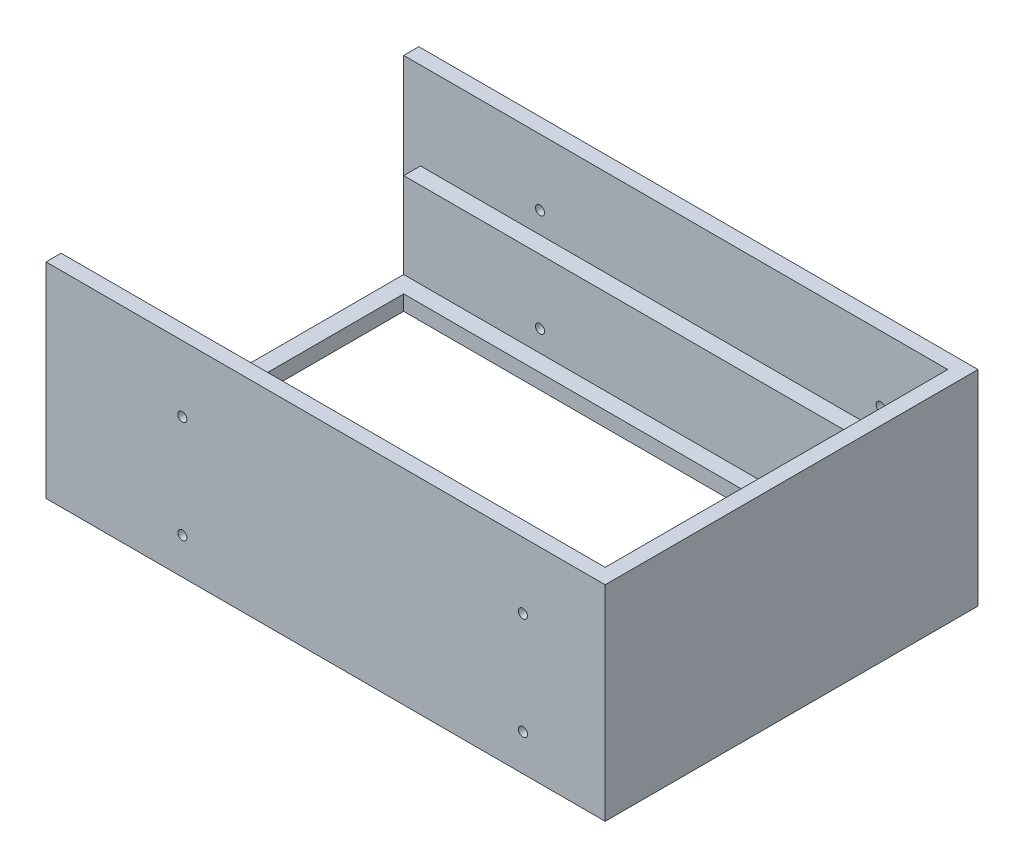
SolidWorks part; units mm, degrees
ref_plane "Front Plane" through (0, 0, 0) normal (0, 0, 1) x (1, 0, 0)
ref_plane "Top Plane" through (0, 0, 0) normal (0, 1, 0) x (1, 0, 0)
ref_plane "Right Plane" through (0, 0, 0) normal (1, 0, 0) x (0, 0, -1)
sketch "Sketch1" plane through (0, 0, 0) normal (0, 1, 0) x (1, 0, 0)
  line L1 (-83.25, 55.5) -> (83.25, 55.5)
  line L2 (-83.25, 55.5) -> (-83.25, -55.5)
  line L3 (-83.25, -55.5) -> (83.25, -55.5)
  line L4 (83.25, 55.5) -> (83.25, -55.5)
  line L5 (-83.25, 55.5) -> (83.25, -55.5) construction
  line L6 (-83.25, -55.5) -> (83.25, 55.5) construction
  point P0 (0, 0)
  dimension "D1" = 166.5
  dimension "D2" = 111
extrude "Boss-Extrude1" add sketch "Sketch1" along normal blind 30.5
shell "Shell1" thickness 4.5
sketch "Sketch2" plane through (0, 4.5, 0) normal (0, 1, 0) x (1, 0, 0)
  line L5 (78.75, 51) -> (-83.25, 51) construction
  line L6 (-78.25, 46) -> (78.75, 46)
  line L9 (-78.25, 46) -> (-78.25, -46)
  line L10 (-78.25, -46) -> (78.75, -46)
  line L11 (78.75, 46) -> (78.75, -46)
  line L12 (-83.25, -51) -> (78.75, -51) construction
  line L13 (-83.25, 51) -> (-83.25, -51) construction
  line L14 (78.75, -51) -> (78.75, 51) construction
  point P0 (0, 0)
  dimension "D1" = 5
  dimension "D2" = 5
  dimension "D3" = 5
extrude "Cut-Extrude1" cut sketch "Sketch2" against normal up to next
hole_wizard "Tap Drill for #6-32 Tap1" positions "Sketch4" profile "Sketch5" hole size "#6-32" standard "ANSI Inch"
sketch "Sketch4" plane through (0, 0, -55.5) normal (0, 0, -1) x (-1, 0, 0)
  line L0 (-78.75, 4.5) -> (83.25, 4.5) construction
  line L2 (-78.75, 30.5) -> (-78.75, 4.5) construction
  point P0 (42.66, 10.84)
  point P2 (-58.75, 10.84)
  dimension "D1" = 6.34
  dimension "D2" = 20
  dimension "D3" = 101.41
sketch "Sketch5" plane through (-42.66, 10.84, -55.5) normal (1, 0, 0) x (0, 1, 0)
  line L0 (0, 0) -> (0, 4.5)
  line L1 (0, 4.5) -> (1.3525, 4.5)
  line L2 (1.3525, 4.5) -> (1.3525, 0)
  line L5 (1.3525, 0) -> (0, 0)
  line L11 (0, -6.35) -> (0, 107.95) construction
  dimension "Thru Hole Dia." = 2.7051
  dimension "Thru Hole Depth" = 4.5
mirror "Mirror1" about plane through (0, 0, 0) normal (0, 0, 1) of "Tap Drill for #6-32 Tap1"
pattern_linear "LPattern1" count 2 spacing 30.5 along (0, 1, 0) of bodies 104
combine bodies "Combine1" operation type add bodies to combine 104 105
sketch "Sketch7" plane through (-83.25, 0, 0) normal (-1, 0, 0) x (0, 0, 1)
  line L1 (-51, 30.5) -> (51, 30.5)
  line L2 (-51, 30.5) -> (-51, 35)
  line L3 (-51, 35) -> (51, 35)
  line L4 (51, 30.5) -> (51, 35)
extrude "Cut-Extrude2" cut sketch "Sketch7" against normal up to surface (5 mm away) up to face at (-78.25, 32.75, 0)
sketch "Sketch8" plane through (-78.25, 0, 0) normal (-1, 0, 0) x (0, 0, 1)
  line L0 (-51, 30.5) -> (-46, 35)
  line L1 (-46, 35) -> (-46, 30.5)
  line L2 (-46, 30.5) -> (-51, 30.5)
  line L3 (51, 30.5) -> (46, 30.5)
  line L4 (46, 30.5) -> (46, 35)
  line L5 (46, 35) -> (51, 30.5)
extrude "Cut-Extrude3" cut sketch "Sketch8" against normal up to surface (157 mm away)
equation "\"Drive Lenght\"= 162"
equation "\"Drive Width\" = 102"
equation "\"Drive Thickness\"= 25.5"
equation "\"D1@Sketch1\"=\"Drive Lenght\"+\"Spacer\""
equation "\"D2@Sketch1\"=\"Drive Width\" +\"Spacer\"*2"
equation "\"D1@Boss-Extrude1\"=\"Drive Thickness\"+5"
equation "\"D1@Sketch2\"=5"
equation "\"D2@Sketch2\"=5"
equation "\"D3@Sketch2\"=5"
equation "\"Spacer\"= 4.5"
equation "\"Drive Hole from botton\" = 6.34"
equation "\"Between Drive holes\"= 101.41"
equation "\"Drive hole to fron\"= 20"
equation "\"D1@Sketch4\"=\"Drive Hole from botton\""
equation "\"D2@Sketch4\"=\"Drive hole to fron\""
equation "\"D3@Sketch4\"=\"Between Drive holes\""
equation "\"D3@LPattern1\"=\"Drive Thickness\"+5 "
